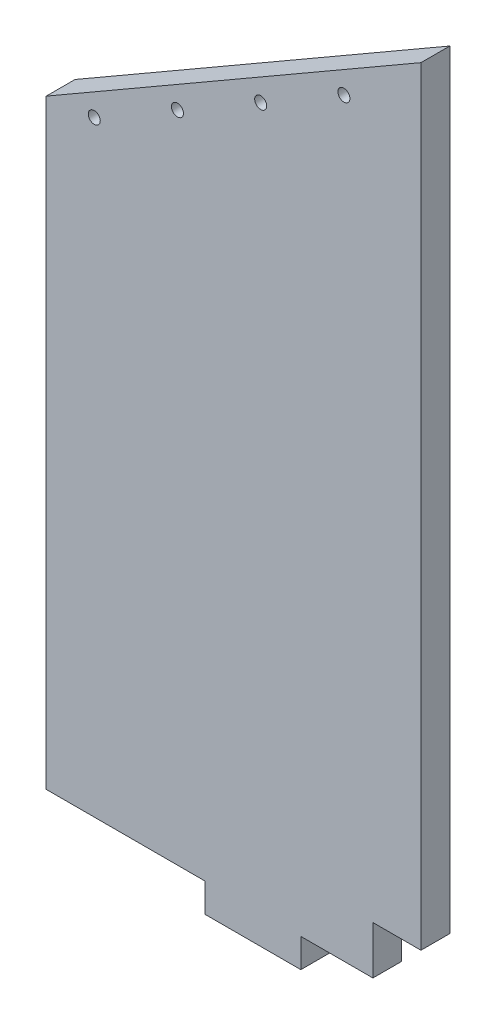
SolidWorks part; units mm, degrees
ref_plane "Plan de face" through (0, 0, 0) normal (0, 0, 1) x (1, 0, 0)
ref_plane "Plan de dessus" through (0, 0, 0) normal (0, 1, 0) x (1, 0, 0)
ref_plane "Plan de droite" through (0, 0, 0) normal (1, 0, 0) x (0, 0, -1)
sketch "Esquisse1" plane through (0, 0, 0) normal (0, 0, 1) x (1, 0, 0)
  line L0 (-78, 0) -> (-78, 124.9667)
  line L1 (0, 0) -> (-78, 0)
  line L2 (0, 0) -> (0, 170)
  line L3 (-78, 124.9667) -> (0, 170)
  dimension "D1" = 120
  dimension "D2" = 78
  dimension "D3" = 170
extrude "Boss.-Extru.1" add sketch "Esquisse1" along normal blind 6
sketch "Esquisse2" plane through (0, 0, 6) normal (0, 0, 1) x (1, 0, 0)
  line L0 (0, 170) -> (-78, 124.9667) construction
  line L1 (-78, 124.9667) -> (-78, 0) construction
  line L3 (0, 0) -> (-10, 0)
  line L4 (0, 0) -> (0, 10)
  line L5 (0, 10) -> (-10, 10)
  line L6 (-10, 0) -> (-10, 10)
  circle A0 centre (-68, 126.1214) radius 1.25
  circle A1 centre (-50.6795, 136.1214) radius 1.25
  circle A2 centre (-16.0385, 156.1214) radius 1.25
  circle A3 centre (-33.359, 146.1214) radius 1.25
  dimension "D1" = 2.5
  dimension "D2" = 2.5
  dimension "D3" = 2.5
  dimension "D5" = 4
  dimension "D10" = 2.5
  dimension "D4" = 4
  dimension "D6" = 4
  dimension "D7" = 10
  dimension "D8" = 20
  dimension "D9" = 20
  dimension "D11" = 4
  dimension "D12" = 20
  dimension "D13" = 10
  dimension "D14" = 10
extrude "Enlèv. mat.-Extru.1" cut sketch "Esquisse2" against normal blind 10
sketch "Esquisse4" plane through (0, 0, 0) normal (0, -1, 0) x (1, 0, 0)
  line L0 (-78, 0) -> (-10, 0) construction
  line L1 (-25, 0) -> (-45, 0)
  line L2 (-25, 0) -> (-25, 6)
  line L3 (-25, 6) -> (-45, 6)
  line L4 (-45, 0) -> (-45, 6)
  line L5 (-78, 6) -> (-10, 6) construction
  line L6 (0, 6) -> (0, 0) construction
  dimension "D1" = 20
  dimension "D2" = 25
extrude "Boss.-Extru.2" add sketch "Esquisse4" along normal blind 6
